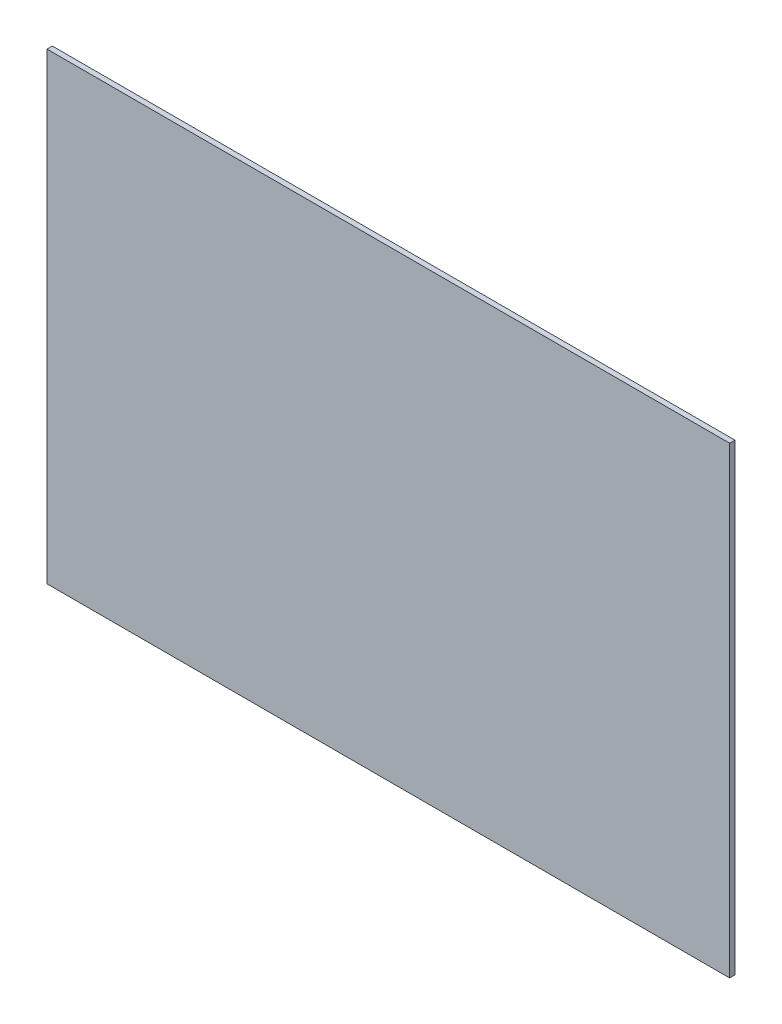
SolidWorks part; units mm, degrees
ref_plane "Plan de face" through (0, 0, 0) normal (0, 0, 1) x (1, 0, 0)
ref_plane "Plan de dessus" through (0, 0, 0) normal (0, 1, 0) x (1, 0, 0)
ref_plane "Plan de droite" through (0, 0, 0) normal (1, 0, 0) x (0, 0, -1)
sketch "Esquisse1" plane through (0, 0, 0) normal (0, 0, 1) x (1, 0, 0)
  line L1 (-256.5, -174) -> (256.5, -174)
  line L2 (-256.5, -174) -> (-256.5, 174)
  line L3 (-256.5, 174) -> (256.5, 174)
  line L4 (256.5, -174) -> (256.5, 174)
  line L5 (-256.5, -174) -> (256.5, 174) construction
  line L6 (-256.5, 174) -> (256.5, -174) construction
  point P0 (0, 0)
  dimension "D1" = 348
  dimension "D2" = 513
extrude "Boss.-Extru.1" add sketch "Esquisse1" along normal blind 4
sketch "Esquisse2" plane through (0, 0, 4) normal (0, 0, 1) x (1, 0, 0)
  line L0 (256.5, 174) -> (-256.5, 174) construction
  line L1 (-248.5, -166) -> (248.5, -166) construction
  line L2 (-248.5, -166) -> (-248.5, 166) construction
  line L3 (-248.5, 166) -> (248.5, 166) construction
  line L4 (248.5, -166) -> (248.5, 166) construction
  line L5 (-248.5, -166) -> (248.5, 166) construction
  line L6 (-248.5, 166) -> (248.5, -166) construction
  line L7 (-256.5, 174) -> (-256.5, -174) construction
  line L8 (256.5, -174) -> (256.5, 174) construction
  point P0 (106.5, 166)
  point P1 (-221.5, 166)
  point P2 (106.5, -166)
  point P3 (-221.5, -166)
  point P4 (0, 0)
  dimension "D1" = 8
  dimension "D2" = 8
  dimension "D3" = 35
  dimension "D4" = 150
hole_wizard "Dégagement M51" positions "Esquisse4" profile "Esquisse3" hole size "M5" standard "JIS"
sketch "Esquisse4" plane through (0, 0, 4) normal (0, 0, 1) x (1, 0, 0)
  point P0 (-140, -191.899)
  point P2 (-140, 191.9)
  point P4 (140, 188.1)
  point P6 (140, -191.9)
sketch "Esquisse3" plane through (-140, -191.899, 4) normal (1, 0, 0) x (0, -1, 0)
  line L0 (0, 0) -> (0, 4)
  line L1 (0, 4) -> (2.75, 4)
  line L2 (2.75, 4) -> (2.75, 0)
  line L5 (2.75, 0) -> (0, 0)
  line L11 (0, -6.35) -> (0, 107.95) construction
  dimension "Diamètre du perçage jusqu'au prochain" = 5.5
  dimension "Profondeur du perçage jusqu'au prochain" = 4
